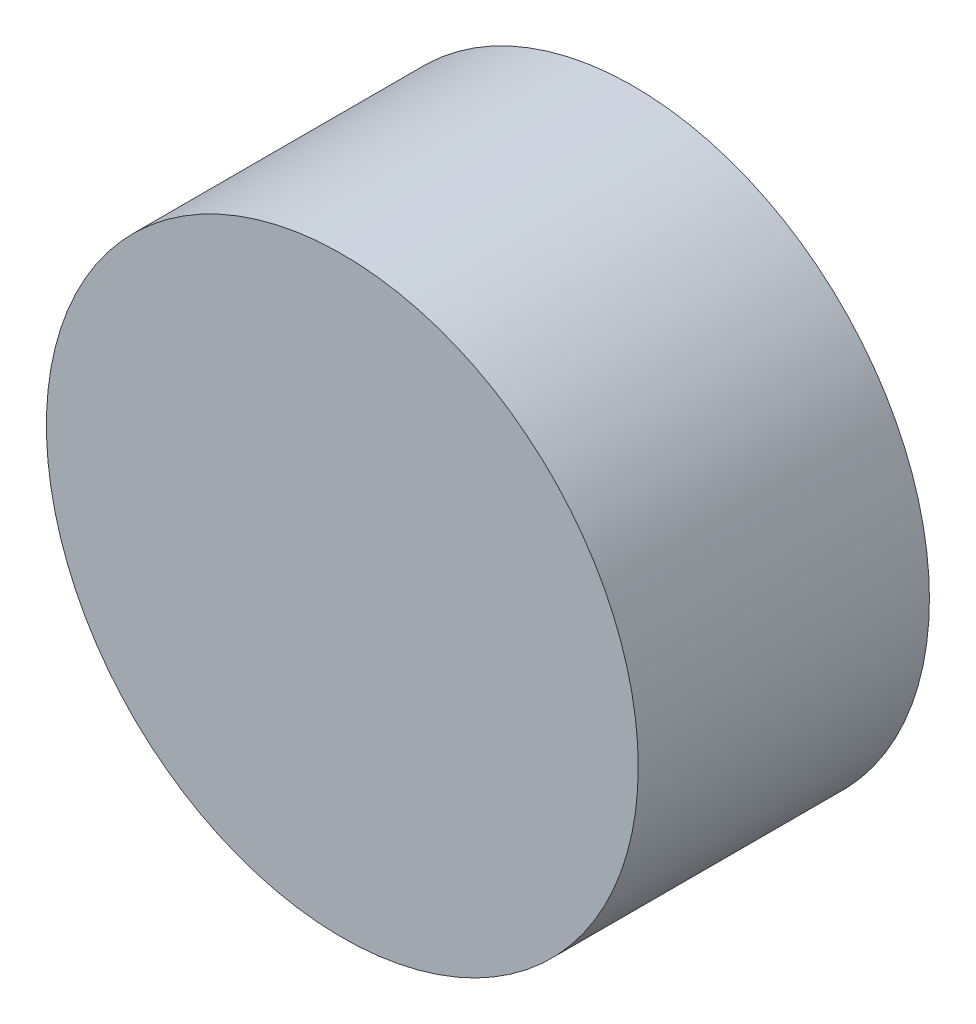
SolidWorks part; units mm, degrees
ref_plane "Plan de face" through (0, 0, 0) normal (0, 0, 1) x (1, 0, 0)
ref_plane "Plan de dessus" through (0, 0, 0) normal (0, 1, 0) x (1, 0, 0)
ref_plane "Plan de droite" through (0, 0, 0) normal (1, 0, 0) x (0, 0, -1)
sketch "Esquisse1" plane through (0, 0, 0) normal (0, 0, 1) x (1, 0, 0)
  circle A0 centre (0, 0) radius 25
  dimension "D1" = 50
extrude "Boss.-Extru.1" add sketch "Esquisse1" along normal blind 24.6
equation "\"Dint\" = 50"
equation "\"epis\" = 24.6"
equation "\"D1@Boss.-Extru.1\"=\"epis\""
equation "\"A\"= 6"
equation "\"B\"= 1"
equation "\"D1@Esquisse1\"=\"Dint\""
